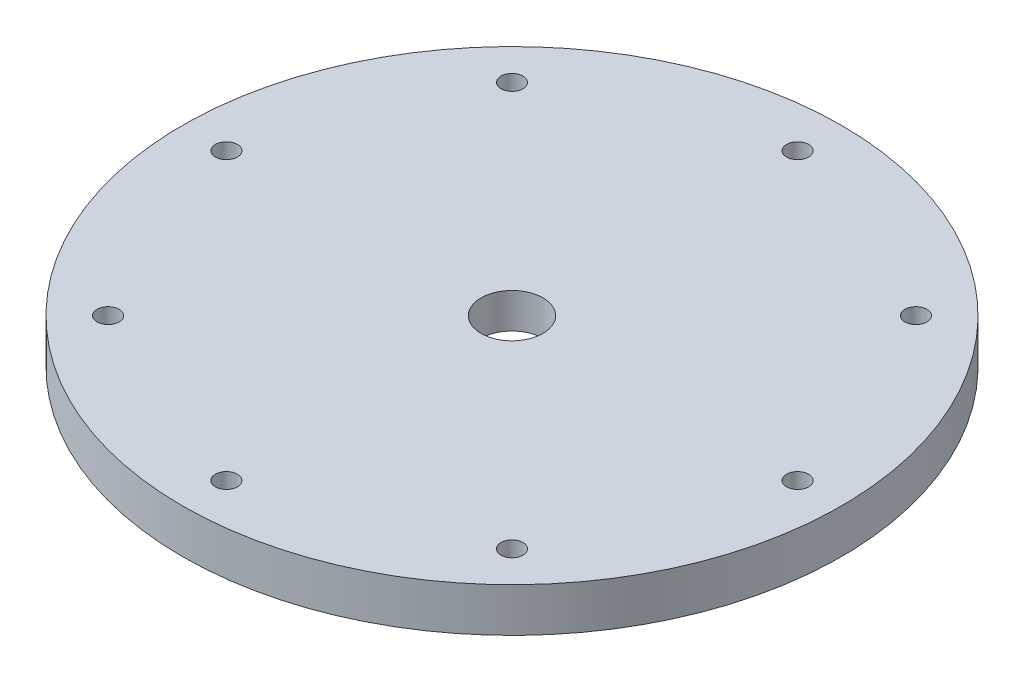
SolidWorks part; units mm, degrees
ref_plane "Front Plane" through (0, 0, 0) normal (0, 0, 1) x (1, 0, 0)
ref_plane "Top Plane" through (0, 0, 0) normal (0, 1, 0) x (1, 0, 0)
ref_plane "Right Plane" through (0, 0, 0) normal (1, 0, 0) x (0, 0, -1)
sketch "Sketch1" plane through (0, 0, 0) normal (0, 1, 0) x (1, 0, 0)
  circle A0 centre (0, 0) radius 95.25
  dimension "D1" = 190.5
extrude "Boss-Extrude1" add sketch "Sketch1" along normal blind 12.7
sketch "Sketch3" plane through (0, 0, 0) normal (0, -1, 0) x (1, 0, 0)
  circle A0 centre (0, 0) radius 69.85
  point P0 (0, 82.55)
  dimension "D2" = 139.7
  dimension "D1" = 82.55
hole_wizard "1/4 (0.25) Diameter Hole1" positions "Sketch4" profile "Sketch5" hole size "1/4" standard "ANSI Inch" end condition through all
sketch "Sketch4" plane through (0, 0, 0) normal (0, -1, 0) x (-1, 0, 0)
  point P0 (0, -82.55)
sketch "Sketch5" plane through (0, 0, 82.55) normal (1, 0, 0) x (0, 0, -1)
  line L0 (0, 0) -> (0, 12.7)
  line L1 (0, 12.7) -> (3.175, 12.7)
  line L2 (3.175, 12.7) -> (3.175, 0)
  line L5 (3.175, 0) -> (0, 0)
  line L11 (0, -6.35) -> (0, 107.95) construction
  dimension "Thru Hole Dia." = 6.35
  dimension "Thru Hole Depth" = 12.7
sketch "Sketch6" plane through (0, 0, 0) normal (1, 0, 0) x (0, 0, -1)
  line L0 (0, 47.6097) -> (0, -58.7833) construction
pattern_circular "CirPattern1" count 8 over 360 about axis through (0, 0, 0) along (0, 1, 0) of "1/4 (0.25) Diameter Hole1"
sketch "Sketch7" plane through (0, 0, 0) normal (0, -1, 0) x (-1, 0, 0)
  circle A1 centre (0, 0) radius 69.9135
  dimension "D1" = 139.827
extrude "Cut-Extrude3" cut sketch "Sketch7" against normal blind 2.54
sketch "Sketch2" plane through (0, 2.54, 0) normal (0, -1, 0) x (1, 0, 0)
  circle A0 centre (0, 0) radius 66.1289
  circle A1 centre (0, 0) radius 68.3133
  dimension "D1" = 136.6266
  dimension "D2" = 2.1844
extrude "Cut-Extrude1" cut sketch "Sketch2" against normal blind 1.3208
sketch "Sketch9" plane through (0, 2.54, 0) normal (0, -1, 0) x (1, 0, 0)
  point P0 (0, 0)
hole_wizard "45/64 (0.70313) Diameter Hole1" positions "Sketch10" profile "Sketch11" hole size "45/64" standard "ANSI Inch" end condition through all
sketch "Sketch10" plane through (0, 2.54, 0) normal (0, -1, 0) x (-1, 0, 0)
  point P0 (0, 0)
sketch "Sketch11" plane through (0, 2.54, 0) normal (1, 0, 0) x (0, 0, -1)
  line L0 (0, 0) -> (0, 10.16)
  line L1 (0, 10.16) -> (8.9298, 10.16)
  line L2 (8.9298, 10.16) -> (8.9298, 0)
  line L5 (8.9298, 0) -> (0, 0)
  line L11 (0, -6.35) -> (0, 107.95) construction
  dimension "Thru Hole Dia." = 17.8595
  dimension "Thru Hole Depth" = 10.16
